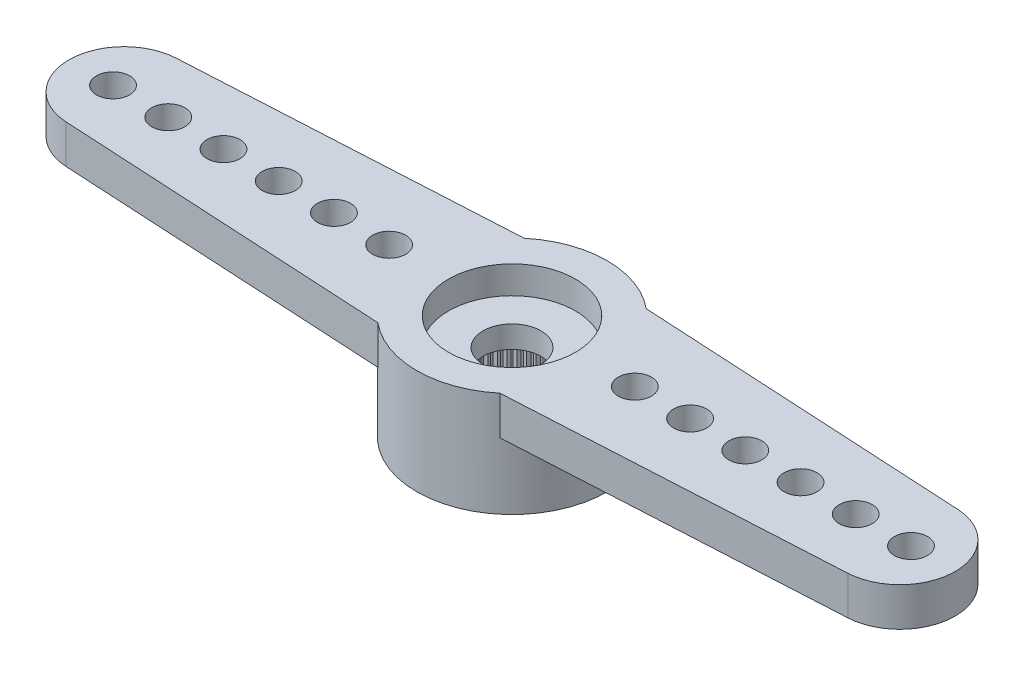
SolidWorks part; units mm, degrees
material "PVC Rígido"
ref_plane "Plano frontal" through (0, 0, 0) normal (0, 0, 1) x (1, 0, 0)
ref_plane "Plano superior" through (0, 0, 0) normal (0, 1, 0) x (1, 0, 0)
ref_plane "Plano direito" through (0, 0, 0) normal (1, 0, 0) x (0, 0, -1)
sketch "Esboço1" plane through (0, 0, 0) normal (0, 1, 0) x (1, 0, 0)
  line L0 (0, 0) -> (-14.05, 0) construction
  line L1 (-14.1591, 1.997) -> (-2.2091, 2.65)
  line L2 (-2.2091, -2.65) -> (-14.1591, -1.997)
  arc A0 (-2.2091, -2.65) -> (-2.2091, 2.65) centre (0, 0) ccw
  arc A1 (-14.1591, 1.997) -> (-14.1591, -1.997) centre (-14.05, 0) ccw
  dimension "D1" = 6.9
  dimension "D2" = 4
  dimension "D3" = 19.5
  dimension "D4" = 5.3
extrude "Ressalto-extrusão1" add sketch "Esboço1" against normal blind 1.4
sketch "Esboço2" plane through (0, -1.4, 0) normal (0, -1, 0) x (1, 0, 0)
  arc A0 (-2.2091, -2.65) -> (-2.2091, 2.65) centre (0, 0) ccw construction
  circle A1 centre (0, 0) radius 3.45
extrude "Ressalto-extrusão2" add sketch "Esboço2" along normal offset from surface (2.4 mm away) 3.8 up to face at (-7.242, 0, 0)
hole_wizard "Furo4" positions "Esboço9" profile "Esboço10" legacy end condition through all
sketch "Esboço9" plane through (0, 0, 0) normal (0, 1, 0) x (1, 0, 0)
  line L1 (-14.45, 0) -> (0, 0) construction
  arc A2 (-14.1591, 1.997) -> (-14.1591, -1.997) centre (-14.05, 0) ccw construction
  point P0 (-14.45, 0)
  point P19 (-16.05, 0)
  dimension "D1" = 1.6
sketch "Esboço10" plane through (-14.45, 0, 0) normal (1, 0, 0) x (0, 0, 1)
  line L0 (0, 0) -> (0, 3.8)
  line L1 (0, 3.8) -> (0.6, 3.8)
  line L2 (0.6, 3.8) -> (0.6, 0)
  line L3 (0.6, 0) -> (0, 0)
  line L4 (0, 110) -> (0, -10) construction
  dimension "Diameter" = 1.2
  dimension "Depth" = 3.8
pattern_linear "Padrão linear1" count 6 spacing 2 along (1, 0, 0) of "Furo4"
pattern_circular "PadrãoCircular2" count 2 over 360 about axis through (0, 0, 0) along (0, 1, 0) of "Ressalto-extrusão1", "Furo4", "Padrão linear1"
hole_wizard "Furo1" positions "Esboço3" profile "Esboço4" legacy
sketch "Esboço3" plane through (0, -3.8, 0) normal (0, -1, 0) x (-1, 0, 0)
  point P0 (0, 0)
sketch "Esboço4" plane through (0, -3.8, 0) normal (1, 0, 0) x (0, 0, -1)
  line L0 (0, 0) -> (0, 2)
  line L1 (0, 2) -> (2.475, 2)
  line L2 (2.475, 2) -> (2.475, 0)
  line L3 (2.475, 0) -> (0, 0)
  line L4 (0, 110) -> (0, -10) construction
  dimension "Diameter" = 4.95
  dimension "Depth" = 2
hole_wizard "Furo2" positions "Esboço5" profile "Esboço6" legacy
sketch "Esboço5" plane through (0, 0, 0) normal (0, 1, 0) x (1, 0, 0)
  point P0 (0, 0)
sketch "Esboço6" plane through (0, 0, 0) normal (1, 0, 0) x (0, 0, 1)
  line L0 (0, 0) -> (0, 1)
  line L1 (0, 1) -> (2.3, 1)
  line L2 (2.3, 1) -> (2.3, 0)
  line L3 (2.3, 0) -> (0, 0)
  line L4 (0, 110) -> (0, -10) construction
  dimension "Diameter" = 4.6
  dimension "Depth" = 1
hole_wizard "Furo3" positions "Esboço7" profile "Esboço8" legacy end condition through all
sketch "Esboço7" plane through (0, 0, 0) normal (0, 1, 0) x (1, 0, 0)
  point P0 (0, 0)
sketch "Esboço8" plane through (0, 0, 0) normal (1, 0, 0) x (0, 0, 1)
  line L0 (0, 0) -> (0, 3.8)
  line L1 (0, 3.8) -> (1.05, 3.8)
  line L2 (1.05, 3.8) -> (1.05, 0)
  line L3 (1.05, 0) -> (0, 0)
  line L4 (0, 110) -> (0, -10) construction
  dimension "Diameter" = 2.1
  dimension "Depth" = 3.8
sketch "Esboço11" plane through (0, -3.8, 0) normal (0, -1, 0) x (1, 0, 0)
  line L0 (-0.0981, 2.4731) -> (0, 2.375)
  line L1 (0, 2.375) -> (0.0981, 2.4731)
  line L2 (0, 0) -> (0, 2.475) construction
  circle A0 centre (0, 0) radius 2.375 construction
  circle A1 centre (0, 0) radius 2.475
  arc A2 (0.0981, 2.4731) -> (-0.0981, 2.4731) centre (0, 0) ccw
  dimension "D3" = 4.75
  dimension "D2" = 0.1
  dimension "D1" = 0
extrude "Ressalto-extrusão3" add sketch "Esboço11" against normal up to surface (2 mm away) up to face at (0, -1.8, 1.05)
pattern_circular "PadrãoCircular1" count 60 over 360 about axis through (0, 0, 0) along (0, 1, 0) of "Ressalto-extrusão3"
sketch "Sketch1" plane through (0, 0, 0) normal (0, 1, 0) x (1, 0, 0)
  line L0 (-2.3, 0) -> (2.3, 0) construction
  line L1 (0, 2.3) -> (0, -2.3) construction
  circle A0 centre (0, 0) radius 2.3 construction
  circle A1 centre (0, 0) radius 2.3 construction
sketch "Sketch2" plane through (0, 0, 0) normal (1, 0, 0) x (0, 0, -1)
  line L0 (0, 0) -> (0, -3.8) construction
  line L1 (-3.45, -3.8) -> (3.45, -3.8) construction
